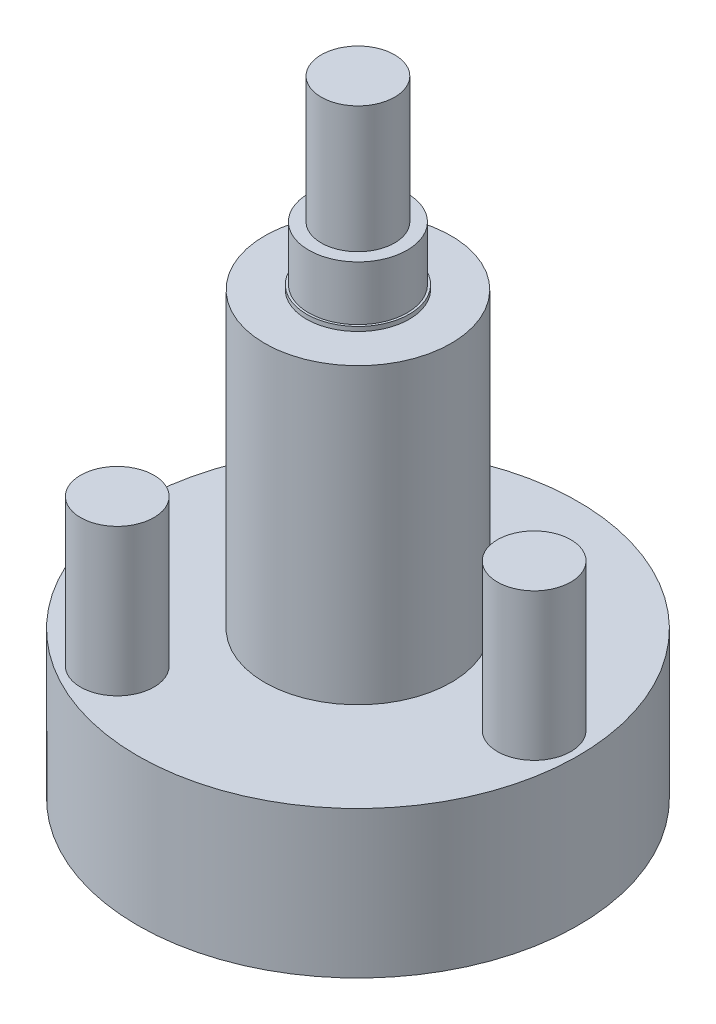
SolidWorks part; units mm, degrees
ref_plane "前视基准面" through (0, 0, 0) normal (0, 0, 1) x (1, 0, 0)
ref_plane "上视基准面" through (0, 0, 0) normal (0, 1, 0) x (1, 0, 0)
ref_plane "右视基准面" through (0, 0, 0) normal (1, 0, 0) x (0, 0, -1)
other "Configuration Table"
sketch "草图1" plane through (0, 0, 0) normal (0, 1, 0) x (1, 0, 0)
  circle A0 centre (0, 0) radius 2.5
  dimension "D1" = 5
extrude "凸台-拉伸1" add sketch "草图1" along normal blind 5
ref_plane "基准面1" through (0, 5, 0) normal (0, 1, 0) x (1, 0, 0)
sketch "草图2" plane through (0, 5, 0) normal (0, 1, 0) x (1, 0, 0)
  circle A0 centre (0, 0) radius 3.5
  dimension "D1" = 7
extrude "凸台-拉伸2" add sketch "草图2" along normal blind 0.3
ref_plane "基准面2" through (0, 5.3, 0) normal (0, 1, 0) x (1, 0, 0)
sketch "草图3" plane through (0, 5.3, 0) normal (0, 1, 0) x (1, 0, 0)
  circle A0 centre (0, 0) radius 15
  dimension "D1" = 30
extrude "凸台-拉伸3" add sketch "草图3" along normal blind 10
ref_plane "基准面3" through (0, 15.3, 0) normal (0, 1, 0) x (1, 0, 0)
sketch "草图4" plane through (0, 15.3, 0) normal (0, 1, 0) x (1, 0, 0)
  circle A0 centre (0, 0) radius 6.35
  dimension "D1" = 12.7
extrude "凸台-拉伸4" add sketch "草图4" along normal blind 10
ref_plane "基准面4" through (0, 25.3, 0) normal (0, 1, 0) x (1, 0, 0)
sketch "草图5" plane through (0, 25.3, 0) normal (0, 1, 0) x (1, 0, 0)
  circle A0 centre (0, 0) radius 6.35
  dimension "D1" = 12.7
extrude "凸台-拉伸5" add sketch "草图5" along normal blind 10
ref_plane "基准面5" through (0, 35.3, 0) normal (0, 1, 0) x (1, 0, 0)
sketch "草图6" plane through (0, 35.3, 0) normal (0, 1, 0) x (1, 0, 0)
  circle A0 centre (0, 0) radius 3.5
  dimension "D1" = 7
extrude "凸台-拉伸6" add sketch "草图6" along normal blind 0.3
ref_plane "基准面6" through (0, 35.6, 0) normal (0, 1, 0) x (1, 0, 0)
sketch "草图7" plane through (0, 35.6, 0) normal (0, 1, 0) x (1, 0, 0)
  circle A0 centre (0, 0) radius 3.35
  dimension "D1" = 6.7
extrude "凸台-拉伸7" add sketch "草图7" along normal blind 3.7
ref_plane "基准面7" through (0, 39.3, 0) normal (0, 1, 0) x (1, 0, 0)
sketch "草图8" plane through (0, 39.3, 0) normal (0, 1, 0) x (1, 0, 0)
  circle A0 centre (0, 0) radius 2.5
  dimension "D1" = 5
extrude "凸台-拉伸8" add sketch "草图8" along normal blind 3
cosmetic thread "装饰螺纹线1" parameters "D1"=8.6, "D2"=4
ref_plane "基准面8" through (0, 5, 0) normal (0, -1, 0) x (-1, 0, 0)
sketch "草图9" plane through (0, 5, 0) normal (0, -1, 0) x (-1, 0, 0)
  circle A0 centre (0, 0) radius 3.35
  dimension "D1" = 6.7
extrude "凸台-拉伸9" add sketch "草图9" along normal blind 3.7
ref_plane "基准面9" through (0, 42.3, 0) normal (0, 1, 0) x (1, 0, 0)
sketch "草图10" plane through (0, 42.3, 0) normal (0, 1, 0) x (1, 0, 0)
  circle A0 centre (0, 0) radius 2.5
extrude "凸台-拉伸10" add sketch "草图10" along normal blind 5.6
sketch "草图11" plane through (0, 15.3, 0) normal (0, 1, 0) x (1, 0, 0)
  line L0 (0, 0) -> (15, 0) construction
  circle A0 centre (0, 0) radius 15 construction
  circle A1 centre (12, 0) radius 2.5
  dimension "D1" = 5
  dimension "D2" = 12
extrude "凸台-拉伸11" add sketch "草图11" along normal blind 10
pattern_circular "阵列(圆周)1" count 3 over 360 about axis through (0, 0, 0) along (0, 1, 0) of "凸台-拉伸11"
